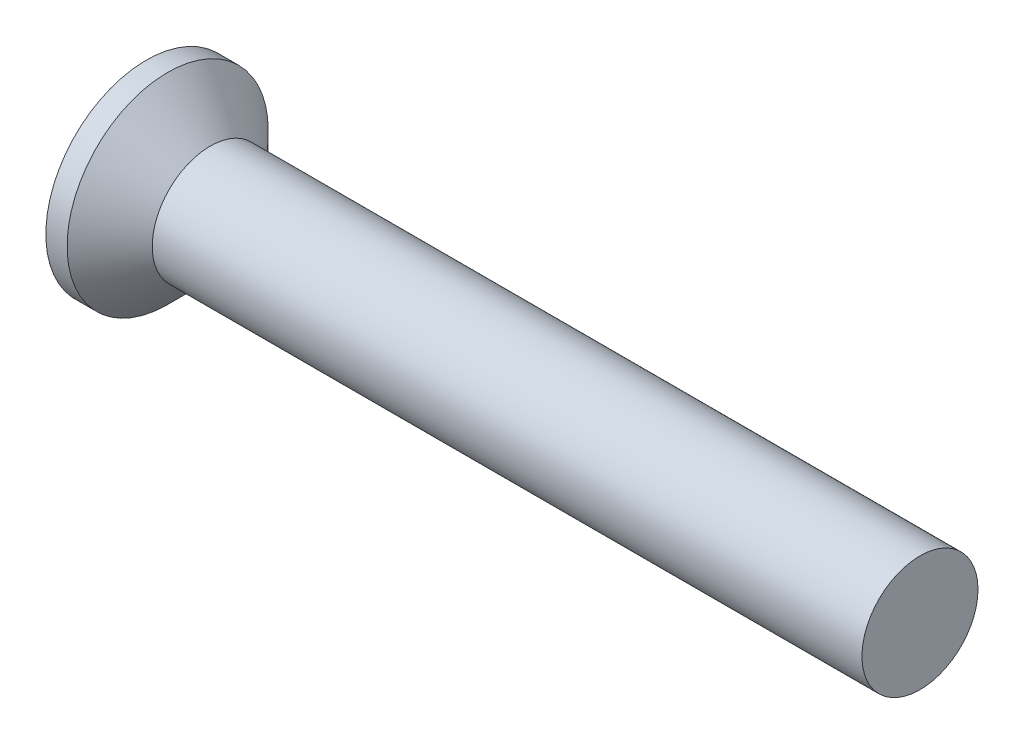
SolidWorks part; units mm, degrees
ref_plane "Front" through (0, 0, 0) normal (0, 0, 1) x (1, 0, 0)
ref_plane "Top" through (0, 0, 0) normal (0, 1, 0) x (1, 0, 0)
ref_plane "Right" through (0, 0, 0) normal (1, 0, 0) x (0, 0, -1)
sketch "Sketch1" plane through (0, 0, 0) normal (0, 0, 1) x (1, 0, 0)
  line L0 (20, 1.5) -> (2.65, 1.5)
  line L1 (2.65, 1.5) -> (1.65, 1.5)
  line L2 (1.65, 1.5) -> (0.55, 2.6)
  line L3 (0.55, 2.6) -> (0, 2.6)
  line L4 (20, 1.5) -> (20, 0)
  line L5 (4.5158, 0) -> (-89.8219, 0) construction
  line L6 (20, 0) -> (0, 0)
  line L7 (0, 2.6) -> (0, 0)
  dimension "D1" = 45
  dimension "dk" = 5.2
  dimension "l" = 20
  dimension "k" = 1.65
  dimension "a" = 1
  dimension "d" = 3
revolve "Base" add sketch "Sketch1" angle 360 about L5
cosmetic thread "ThreadCosmetic1" parameters "bb"=18.35
sketch "Sketch6" plane through (0, 0, 0) normal (1, 0, 0) x (0, 0, -1)
  line L0 (-1.9271, 0) -> (2.0512, 0) construction
  line L1 (0, 1.8651) -> (0, -2.0207) construction
  line L2 (0.32, 0.32) -> (0.32, 1.6)
  line L3 (0.32, 1.6) -> (-0.32, 1.6)
  line L4 (-0.32, 0.32) -> (-0.32, 1.6)
  line L5 (0.32, 0.32) -> (1.6, 0.32)
  line L6 (1.6, 0.32) -> (1.6, -0.32)
  line L7 (-1.6, 0.32) -> (-1.6, -0.32)
  line L8 (-0.32, 0.32) -> (-1.6, 0.32)
  line L9 (-0.32, -0.32) -> (-1.6, -0.32)
  line L10 (0.32, -0.32) -> (1.6, -0.32)
  line L11 (-0.32, -0.32) -> (-0.32, -1.6)
  line L12 (0.32, -1.6) -> (-0.32, -1.6)
  line L13 (0.32, -0.32) -> (0.32, -1.6)
  point P16 (-1.6, 0)
  point P17 (1.6, 0)
extrude "CrossRecess" cut sketch "Sketch6" along normal blind 0.825
draft "Draft9" type of draft neutral plane draft angle 30 faces to draft 4 face at (0.4125, 1.6, 0) face at (0.4125, 0, 1.6) face at (0.4125, -1.6, 0) face at (0.4125, 0, -1.6) neutral plane through (0, 2.6, 0) neutral plane normal (-1, 0, 0) parameters "D1"=30
fillet "Fillet5" radius 0.3 4 edges at (0.4125, -0.32, -0.32) (0.4125, 0.32, -0.32) (0.4125, 0.32, 0.32) (0.4125, -0.32, 0.32)
sketch "Sketch7" plane through (0, 0, 0) normal (1, 0, 0) x (0, 0, -1)
  line L0 (-2.0126, 0) -> (1.9757, 0) construction
  line L1 (0, 1.9314) -> (0, -2.0126) construction
  line L2 (0, 0) -> (1.5555, 1.5555) construction
  line L3 (0, 0.4782) -> (1.1314, 1.1314)
  line L4 (-1.5402, 1.5402) -> (0, 0) construction
  line L5 (0.4782, 0) -> (1.1314, 1.1314)
  line L6 (0, -0.4782) -> (1.1314, -1.1314)
  line L7 (0.4782, 0) -> (1.1314, -1.1314)
  line L8 (-0.4782, 0) -> (-1.1314, -1.1314)
  line L9 (0, -0.4782) -> (-1.1314, -1.1314)
  line L10 (-0.4782, 0) -> (-1.1314, 1.1314)
  line L11 (0, 0.4782) -> (-1.1314, 1.1314)
  dimension "D3" = 15
  dimension "m" = 3.2
extrude "Cut-Extrude3" [suppressed] cut sketch "Sketch7" along normal blind 10 draft 20
sketch "Sketch8" plane through (0, 0, 0) normal (0, 0, 1) x (1, 0, 0)
  line L0 (-5, 1.7705) -> (-6.25, 1.5)
  line L1 (-6.25, 1.5) -> (1.65, 1.5)
  line L3 (20, -1.5) -> (20, 1.5) construction
  line L6 (1.65, 1.5) -> (1.65, 6.5)
  line L7 (1.65, 6.5) -> (-5, 6.5)
  line L8 (-5, 6.5) -> (-5, 1.7705)
  line L9 (62.4753, 0.2705) -> (52.9594, 0.2705) construction
  dimension "D1" = 5
  dimension "x" = 1.25
  dimension "d" = 3
  dimension "THD_MINOR" = 2.459
  dimension "b" = 25
sketch "Sketch9" plane through (0, 0, 0) normal (0, 0, 1) x (1, 0, 0)
  line L0 (20, 1.2657) -> (20.1352, 1.5)
  line L1 (20.1352, 1.5) -> (20.1352, 1.7705)
  line L2 (20.1352, 1.7705) -> (19.8648, 1.7705)
  line L3 (19.8648, 1.7705) -> (19.8648, 1.5)
  line L4 (19.8648, 1.5) -> (20, 1.2657)
  line L5 (0, 0) -> (73.843, 0) construction
  line L6 (20, -1.5) -> (20, 1.5) construction
  dimension "D1" = 3
  dimension "D2" = 0.2705
revolve "Cut-Revolve10" [suppressed] cut sketch "Sketch9" angle 360 about L5
pattern_linear "LPattern10" [suppressed] count 57 spacing 0.3246 along (1, 0, 0)
equation "\"D1@Sketch6\" = \"m@Sketch6\" / 5"
equation "\"D1@CrossRecess\" = \"k@Sketch1\" / 2"
equation "\"D1@Sketch9\" = \"d@Sketch1\""
equation "\"D2@Sketch9\" =  ( \"d@Sketch1\" - \"THD_MINOR@ThreadCosmetic1\" )  / 2"
equation "\"D3@LPattern10\" = \"D2@Sketch9\" * 1.2"
equation "\"D1@LPattern10\" = \"bb@ThreadCosmetic1\" / \"D3@LPattern10\" "
